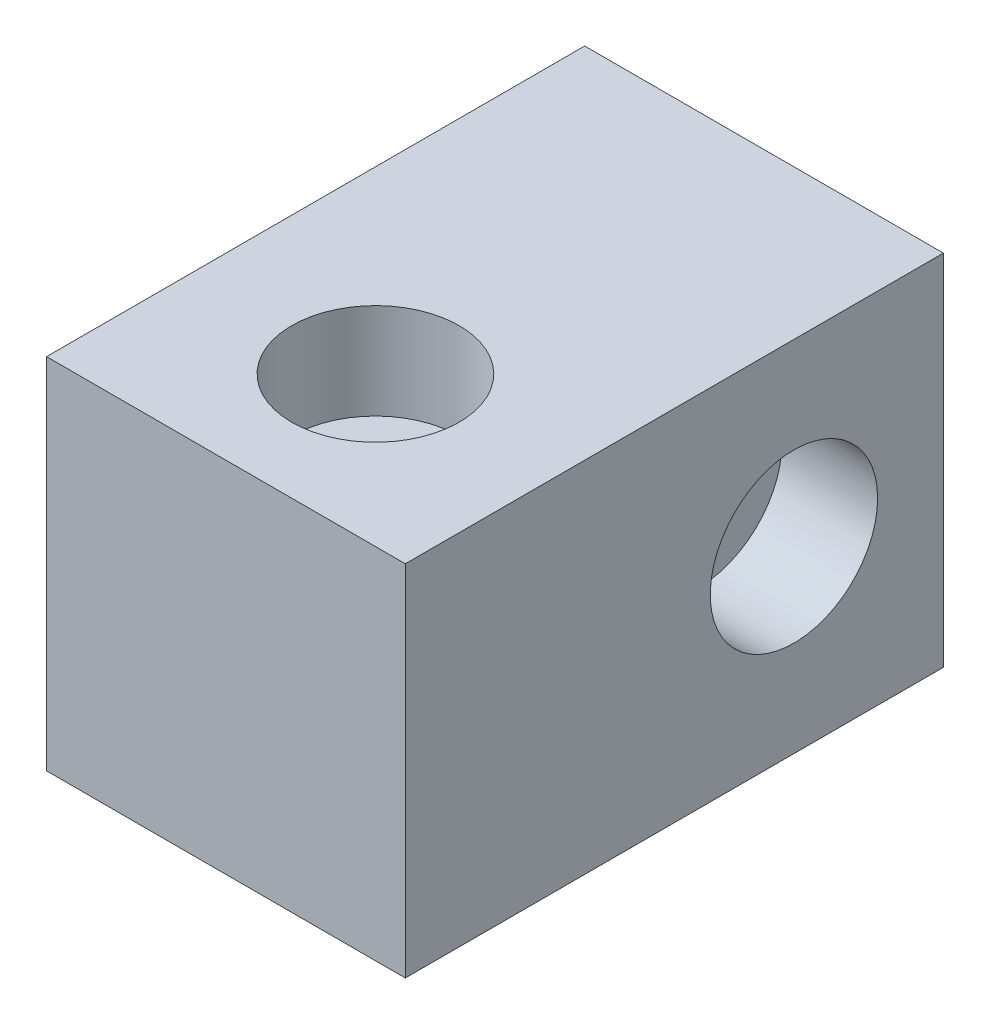
SolidWorks part; units mm, degrees
ref_plane "Front Plane" through (0, 0, 0) normal (0, 0, 1) x (1, 0, 0)
ref_plane "Top Plane" through (0, 0, 0) normal (0, 1, 0) x (1, 0, 0)
ref_plane "Right Plane" through (0, 0, 0) normal (1, 0, 0) x (0, 0, -1)
sketch "Sketch1" plane through (0, 0, 0) normal (0, 1, 0) x (1, 0, 0)
  line L1 (0, 0) -> (15, 0)
  line L2 (0, 0) -> (0, 22.5)
  line L3 (0, 22.5) -> (15, 22.5)
  line L4 (15, 0) -> (15, 22.5)
extrude "Boss-Extrude1" add sketch "Sketch1" along normal blind 15
sketch "Sketch2" plane through (0, 15, 0) normal (0, 1, 0) x (1, 0, 0)
  line L0 (0, 0) -> (15, 0) construction
  line L2 (15, 0) -> (15, 22.5) construction
  circle A0 centre (7.5, 6.25) radius 2
  dimension "D1" = 6.25
  dimension "D2" = 7.5
extrude "Cut-Extrude1" cut sketch "Sketch2" against normal through all
sketch "Sketch3" plane through (0, 0, 0) normal (-1, 0, 0) x (0, 0, 1)
  line L0 (-22.5, 15) -> (0, 15) construction
  line L1 (-22.5, 15) -> (-22.5, 0) construction
  circle A0 centre (-16.25, 7.5) radius 2
  dimension "D1" = 7.5
  dimension "D2" = 6.25
extrude "Cut-Extrude2" cut sketch "Sketch3" against normal through all
sketch "Sketch4" plane through (0, 15, 0) normal (0, 1, 0) x (1, 0, 0)
  circle A0 centre (7.5, 6.25) radius 3.5
extrude "Cut-Extrude3" cut sketch "Sketch4" against normal blind 4
sketch "Sketch5" plane through (15, 0, 0) normal (1, 0, 0) x (0, 0, -1)
  circle A0 centre (16.25, 7.5) radius 3.5
extrude "Cut-Extrude4" cut sketch "Sketch5" against normal blind 4
